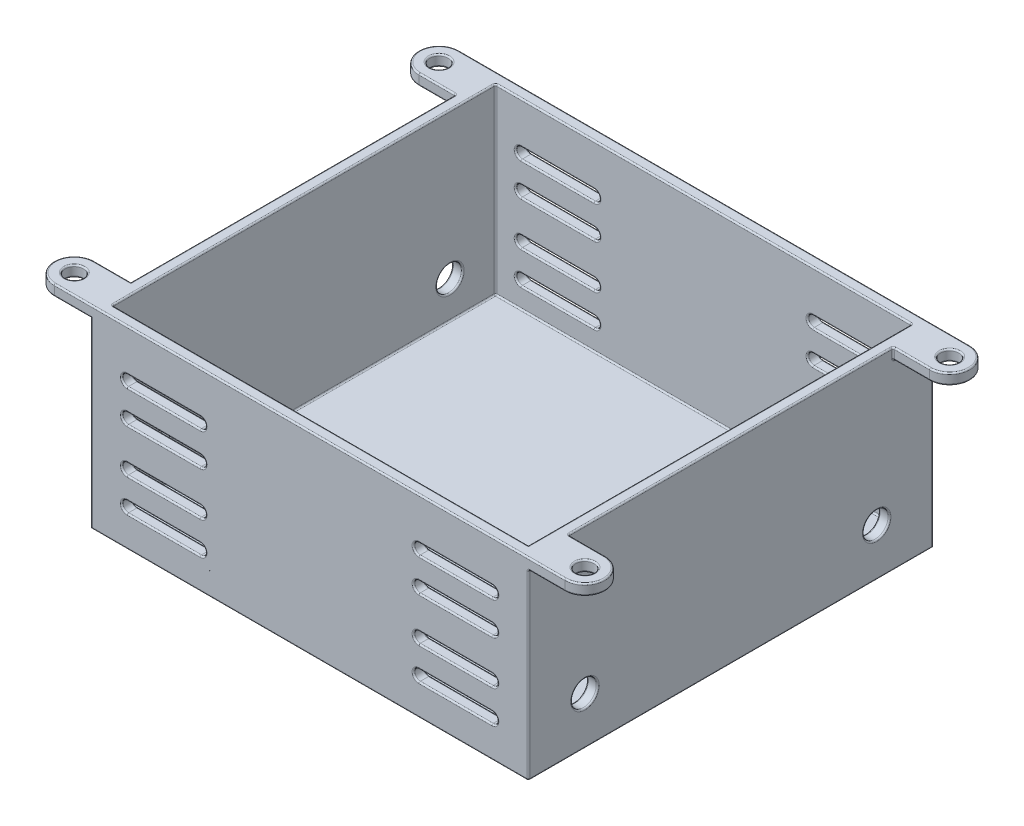
SolidWorks part; units mm, degrees
ref_plane "Front Plane" through (0, 0, 0) normal (0, 0, 1) x (1, 0, 0)
ref_plane "Top Plane" through (0, 0, 0) normal (0, 1, 0) x (1, 0, 0)
ref_plane "Right Plane" through (0, 0, 0) normal (1, 0, 0) x (0, 0, -1)
sketch "Sketch1" plane through (0, 0, 0) normal (0, 1, 0) x (1, 0, 0)
  line L0 (-35, 27.75) -> (35, 27.75) construction
  line L1 (-35, 25) -> (35, 25) construction
  line L2 (-35, 25) -> (-35, -25) construction
  line L3 (-35, -25) -> (35, -25) construction
  line L4 (35, 25) -> (35, -25) construction
  line L5 (-35, 25) -> (35, -25) construction
  line L6 (-35, -25) -> (35, 25) construction
  line L7 (-30, 27.75) -> (-30, -27.75)
  line L8 (35, -27.75) -> (-35, -27.75) construction
  line L9 (-30, -27.75) -> (30, -27.75)
  line L10 (30, -27.75) -> (30, 27.75)
  line L11 (30, 27.75) -> (-30, 27.75)
  line L12 (-35, 22.25) -> (-30, 22.25)
  line L13 (35, 22.25) -> (30, 22.25)
  line L14 (-35, -22.25) -> (-30, -22.25)
  line L15 (35, -22.25) -> (30, -22.25)
  line L16 (28.5, 26.25) -> (-28.5, 26.25)
  line L17 (-28.5, 26.25) -> (-28.5, -26.25)
  line L18 (-28.5, -26.25) -> (28.5, -26.25)
  line L19 (28.5, -26.25) -> (28.5, 26.25)
  circle A0 centre (35, 25) radius 1.25
  circle A1 centre (35, -25) radius 1.25
  circle A2 centre (-35, -25) radius 1.25
  circle A3 centre (-35, 25) radius 1.25
  circle A4 centre (-35, 25) radius 2.75
  circle A5 centre (35, 25) radius 2.75
  circle A6 centre (35, -25) radius 2.75
  circle A7 centre (-35, -25) radius 2.75
  point P0 (0, 0)
  point P24 (0, 27.75)
  dimension "D3" = 2.5
  dimension "D1" = 70
  dimension "D2" = 50
  dimension "D5" = 60
  dimension "D4" = 1.5
  dimension "D6" = 1.5
extrude "Boss-Extrude1" add sketch "Sketch1" against normal blind 25 contours L10 L11 L7 L9 L19 L18 L17 L16
sketch "Sketch2" plane through (0, -25, 0) normal (0, -1, 0) x (1, 0, 0)
  line L4 (30, -27.75) -> (30, 27.75)
  line L5 (30, 27.75) -> (-30, 27.75)
  line L6 (-30, 27.75) -> (-30, -27.75)
  line L7 (-30, -27.75) -> (30, -27.75)
  line L8 (30, -27.75) -> (30, 27.75)
  line L9 (30, 27.75) -> (-30, 27.75)
  line L10 (-30, 27.75) -> (-30, -27.75)
  line L11 (-30, -27.75) -> (30, -27.75)
  dimension "D1" = 0
extrude "Boss-Extrude2" add sketch "Sketch2" along normal blind 1.5
sketch "Sketch3" plane through (0, 0, 0) normal (0, 1, 0) x (1, 0, 0)
  line L0 (35, 22.25) -> (30, 22.25) construction
  line L1 (35, -22.25) -> (30, -22.25) construction
  line L2 (-35, -22.25) -> (-30, -22.25) construction
  line L3 (-35, 22.25) -> (-30, 22.25) construction
  line L4 (30, -27.75) -> (30, 27.75)
  line L5 (30, 27.75) -> (-30, 27.75)
  line L6 (-30, 27.75) -> (-30, -27.75)
  line L7 (-30, -27.75) -> (30, -27.75)
  line L8 (30, -27.75) -> (30, -22.25)
  line L10 (-30, 27.75) -> (-30, 22.25)
  line L12 (35, 22.25) -> (30, 22.25)
  line L13 (35, -22.25) -> (30, -22.25)
  line L14 (-35, -22.25) -> (-30, -22.25)
  line L15 (-35, 22.25) -> (-30, 22.25)
  line L16 (-35, 27.75) -> (-30, 27.75)
  line L17 (-35, -27.75) -> (-30, -27.75)
  line L18 (30, -27.75) -> (35, -27.75)
  line L19 (30, 27.75) -> (35, 27.75)
  line L20 (-30, -22.25) -> (-30, -27.75)
  line L21 (30, 22.25) -> (30, 27.75)
  circle A0 centre (35, 25) radius 1.25 construction
  circle A1 centre (35, 25) radius 2.75 construction
  circle A2 centre (35, -25) radius 1.25 construction
  circle A3 centre (35, -25) radius 2.75 construction
  circle A4 centre (-35, -25) radius 1.25 construction
  circle A5 centre (-35, -25) radius 2.75 construction
  circle A6 centre (-35, 25) radius 1.25 construction
  circle A7 centre (-35, 25) radius 2.75 construction
  circle A8 centre (35, 25) radius 1.25
  arc A9 (35, 22.25) -> (35, 27.75) centre (35, 25) ccw
  circle A10 centre (35, -25) radius 1.25
  arc A11 (35, -27.75) -> (35, -22.25) centre (35, -25) ccw
  circle A12 centre (-35, -25) radius 1.25
  arc A13 (-35, -22.25) -> (-35, -27.75) centre (-35, -25) ccw
  circle A14 centre (-35, 25) radius 1.25
  arc A15 (-35, 27.75) -> (-35, 22.25) centre (-35, 25) ccw
  dimension "D1" = 0
extrude "Boss-Extrude3" add sketch "Sketch3" against normal blind 1.5
sketch "Sketch4" plane through (0, 0, 0) normal (0, 0, 1) x (1, 0, 0)
  line L0 (30, -14) -> (-30, -14) construction
  line L1 (30, -26.5) -> (30, -1.5) construction
  line L2 (-30, -26.5) -> (-30, -1.5) construction
  line L3 (-25, -6.5) -> (-15, -6.5) construction
  line L4 (-25, -5.75) -> (-15, -5.75)
  line L5 (-25, -7.25) -> (-15, -7.25)
  line L6 (-25, -11) -> (-15, -11) construction
  line L7 (-25, -10.25) -> (-15, -10.25)
  line L8 (-25, -11.75) -> (-15, -11.75)
  line L9 (0, -14) -> (0, -21.2238) construction
  line L10 (-25, -21.5) -> (-15, -21.5) construction
  line L11 (-25, -22.25) -> (-15, -22.25)
  line L12 (-25, -20.75) -> (-15, -20.75)
  line L13 (-25, -17) -> (-15, -17) construction
  line L14 (-25, -17.75) -> (-15, -17.75)
  line L15 (-25, -16.25) -> (-15, -16.25)
  line L16 (25, -6.5) -> (15, -6.5) construction
  line L17 (25, -5.75) -> (15, -5.75)
  line L18 (25, -7.25) -> (15, -7.25)
  line L19 (25, -11) -> (15, -11) construction
  line L20 (25, -10.25) -> (15, -10.25)
  line L21 (25, -11.75) -> (15, -11.75)
  line L22 (25, -21.5) -> (15, -21.5) construction
  line L23 (25, -22.25) -> (15, -22.25)
  line L24 (25, -20.75) -> (15, -20.75)
  line L25 (25, -17) -> (15, -17) construction
  line L26 (25, -17.75) -> (15, -17.75)
  line L27 (25, -16.25) -> (15, -16.25)
  arc A0 (-25, -5.75) -> (-25, -7.25) centre (-25, -6.5) ccw
  arc A1 (-15, -7.25) -> (-15, -5.75) centre (-15, -6.5) ccw
  arc A2 (-25, -10.25) -> (-25, -11.75) centre (-25, -11) ccw
  arc A3 (-15, -11.75) -> (-15, -10.25) centre (-15, -11) ccw
  arc A4 (-25, -22.25) -> (-25, -20.75) centre (-25, -21.5) cw
  arc A5 (-15, -20.75) -> (-15, -22.25) centre (-15, -21.5) cw
  arc A6 (-25, -17.75) -> (-25, -16.25) centre (-25, -17) cw
  arc A7 (-15, -16.25) -> (-15, -17.75) centre (-15, -17) cw
  arc A8 (25, -5.75) -> (25, -7.25) centre (25, -6.5) cw
  arc A9 (15, -7.25) -> (15, -5.75) centre (15, -6.5) cw
  arc A10 (25, -10.25) -> (25, -11.75) centre (25, -11) cw
  arc A11 (15, -11.75) -> (15, -10.25) centre (15, -11) cw
  arc A12 (25, -22.25) -> (25, -20.75) centre (25, -21.5) ccw
  arc A13 (15, -20.75) -> (15, -22.25) centre (15, -21.5) ccw
  arc A14 (25, -17.75) -> (25, -16.25) centre (25, -17) ccw
  arc A15 (15, -16.25) -> (15, -17.75) centre (15, -17) ccw
  point P8 (-20, -6.5)
  point P16 (-20, -11)
  point P25 (-20, -21.5)
  point P32 (-20, -17)
  point P39 (20, -6.5)
  point P46 (20, -11)
  point P53 (20, -21.5)
  point P60 (20, -17)
  dimension "D2" = 1.5
  dimension "D1" = 10
  dimension "D3" = 7.5
  dimension "D4" = 20
  dimension "D5" = 4.5
extrude "Cut-Extrude1" cut sketch "Sketch4" against normal up to surface and the other way up to surface up to face at (0, -7.375, -27.75) other way up to face at (0, -7.375, 27.75)
sketch "Sketch5" plane through (0, 0, 0) normal (1, 0, 0) x (0, 0, -1)
  line L0 (0, 0) -> (0, -20) construction
  line L1 (-22.25, 0) -> (22.25, 0) construction
  line L2 (0, -20) -> (-20, -20) construction
  circle A0 centre (-20, -20) radius 1.75
  circle A1 centre (20, -20) radius 1.75
  dimension "D1" = 3.5
  dimension "D2" = 20
  dimension "D3" = 20
extrude "Cut-Extrude2" cut sketch "Sketch5" against normal up to surface and the other way up to surface up to face at (-30, -7.375, 0) other way up to face at (30, -7.375, 0)
fillet "Fillet1" radius 0.2 191 edges at (-30, -14, -27.75) (-30, -1.5, -25) (20, -16.25, -27.75) (20, -20.75, -27.75) (20, -10.25, -27.75) (20, -5.75, -27.75) (-20, -16.25, -27.75) (-20, -20.75, -27.75) (-20, -10.25, -27.75) (-20, -5.75, -27.75) (-20, -5.75, 26.25) (20, -10.25, 26.25) (20, -20.75, 26.25) (20, -16.25, 26.25) (-20, -10.25, 26.25) (-20, -20.75, 26.25) (-20, -16.25, 26.25) (20, -5.75, 26.25) (-32.5, -1.5, 22.25) (-32.5, -1.5, -27.75) (32.5, -1.5, -27.75) (32.5, -1.5, 22.25) (-30, -20, -18.25) (30, -20, -21.75) (30, -20, 18.25) (-30, -20, 21.75) (-28.5, -20, -18.25) (28.5, -20, -21.75) (-28.5, -20, 21.75) (28.5, -20, 18.25) (25.75, -17, -27.75) (20, -17.75, -27.75) (14.25, -17, -27.75) (14.25, -17, 27.75) (20, -16.25, 27.75) (25.75, -17, 27.75) (20, -17.75, 27.75) (25.75, -21.5, -27.75) (20, -22.25, -27.75) (14.25, -21.5, -27.75) (14.25, -21.5, 27.75) (20, -20.75, 27.75) (25.75, -21.5, 27.75) (20, -22.25, 27.75) (25.75, -11, -27.75) (20, -11.75, -27.75) (14.25, -11, -27.75) (14.25, -11, 27.75) (20, -10.25, 27.75) (25.75, -11, 27.75) (20, -11.75, 27.75) (25.75, -6.5, -27.75) (20, -7.25, -27.75) (14.25, -6.5, -27.75) (14.25, -6.5, 27.75) (20, -5.75, 27.75) (25.75, -6.5, 27.75) (20, -7.25, 27.75) (-25.75, -17, -27.75) (-14.25, -17, -27.75) (-20, -17.75, -27.75) (-14.25, -17, 27.75) (-20, -17.75, 27.75) (-25.75, -17, 27.75) (-20, -16.25, 27.75) (-25.75, -21.5, -27.75) (-14.25, -21.5, -27.75) (-20, -22.25, -27.75) (-14.25, -21.5, 27.75) (-20, -22.25, 27.75) (-25.75, -21.5, 27.75) (-20, -20.75, 27.75) (-25.75, -11, -27.75) (-14.25, -11, -27.75) (-20, -11.75, -27.75) (-14.25, -11, 27.75) (-20, -11.75, 27.75) (-25.75, -11, 27.75) (-20, -10.25, 27.75) (-20, -5.75, 27.75) (-25.75, -6.5, 27.75) (-20, -7.25, 27.75) (-14.25, -6.5, 27.75) (-20, -7.25, -27.75) (-14.25, -6.5, -27.75) (-25.75, -6.5, -27.75) (-25.75, -6.5, 26.25) (-25.75, -6.5, -26.25) (-20, -5.75, -26.25) (-14.25, -6.5, 26.25) (-14.25, -6.5, -26.25) (-20, -7.25, 26.25) (-20, -7.25, -26.25) (25.75, -11, 26.25) (25.75, -11, -26.25) (20, -11.75, 26.25) (20, -11.75, -26.25) (14.25, -11, 26.25) (14.25, -11, -26.25) (20, -10.25, -26.25) (25.75, -21.5, 26.25) (25.75, -21.5, -26.25) (20, -22.25, 26.25) (20, -22.25, -26.25) (14.25, -21.5, 26.25) (14.25, -21.5, -26.25) (20, -20.75, -26.25) (25.75, -17, 26.25) (25.75, -17, -26.25) (20, -17.75, 26.25) (20, -17.75, -26.25) (14.25, -17, 26.25) (14.25, -17, -26.25) (20, -16.25, -26.25) (-25.75, -11, 26.25) (-25.75, -11, -26.25) (-20, -10.25, -26.25) (-14.25, -11, 26.25) (-14.25, -11, -26.25) (-20, -11.75, 26.25) (-20, -11.75, -26.25) (-25.75, -21.5, 26.25) (-25.75, -21.5, -26.25) (-20, -20.75, -26.25) (-14.25, -21.5, 26.25) (-14.25, -21.5, -26.25) (-20, -22.25, 26.25) (-20, -22.25, -26.25) (-25.75, -17, 26.25) (-25.75, -17, -26.25) (-20, -16.25, -26.25) (-14.25, -17, 26.25) (-14.25, -17, -26.25) (-20, -17.75, 26.25) (-20, -17.75, -26.25) (25.75, -6.5, 26.25) (25.75, -6.5, -26.25) (20, -7.25, 26.25) (20, -7.25, -26.25) (14.25, -6.5, 26.25) (14.25, -6.5, -26.25) (20, -5.75, -26.25) (-32.5, -1.5, 27.75) (-37.75, -1.5, 25) (-37.75, 0, 25) (-32.5, 0, 22.25) (-35, -1.5, 26.25) (-35, 0, 26.25) (-30, -0.75, -22.25) (-32.5, -1.5, -22.25) (-37.75, -1.5, -25) (-32.5, 0, -22.25) (-37.75, 0, -25) (-35, -1.5, -23.75) (-35, 0, -23.75) (30, -0.75, -22.25) (37.75, -1.5, -25) (32.5, -1.5, -22.25) (30, -1.5, -25) (37.75, 0, -25) (32.5, 0, -22.25) (35, -1.5, -23.75) (35, 0, -23.75) (35, -1.5, 26.25) (35, 0, 26.25) (37.75, 0, 25) (37.75, -1.5, 25) (32.5, 0, 22.25) (32.5, -1.5, 27.75) (30, -1.5, 25) (30, -0.75, 22.25) (30, -26.5, 0) (0, -26.5, 27.75) (28.5, 0, 0) (28.5, -25, 0) (0, 0, 26.25) (0, -25, 26.25) (-28.5, 0, 0) (-28.5, -25, 0) (0, 0, -26.25) (0, -25, -26.25) (30, 0, 0) (0, 0, -27.75) (-30, 0, 0) (0, 0, 27.75) (-28.5, -12.5, 26.25) (-28.5, -12.5, -26.25) (28.5, -12.5, -26.25) (30, -14, -27.75) (-30, -14, 27.75) (30, -14, 27.75)
